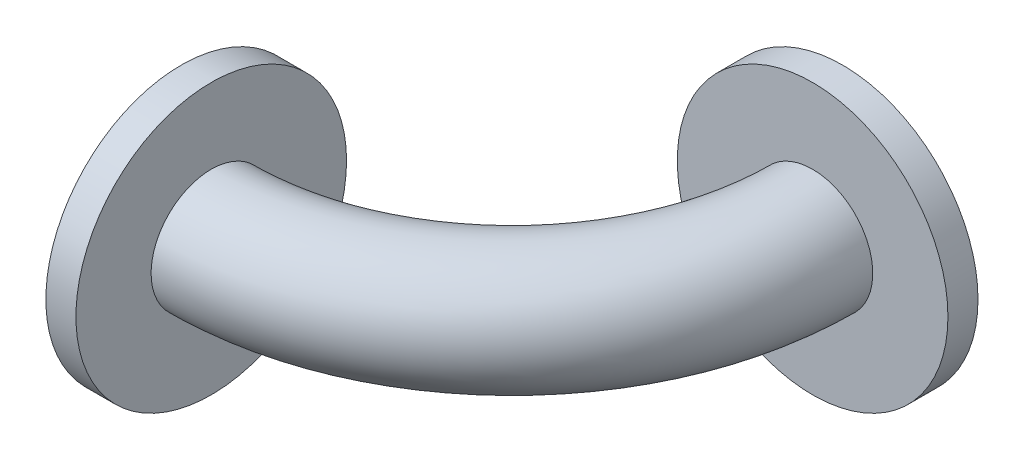
SolidWorks part; units mm, degrees
ref_plane "前视基准面" through (0, 0, 0) normal (0, 0, 1) x (1, 0, 0)
ref_plane "上视基准面" through (0, 0, 0) normal (0, 1, 0) x (1, 0, 0)
ref_plane "右视基准面" through (0, 0, 0) normal (1, 0, 0) x (0, 0, -1)
sketch "草图1" plane through (0, 0, 0) normal (0, 1, 0) x (1, 0, 0)
  arc A0 (40, 0) -> (0, -40) centre (0.0001, -0.0001) cw
sweep "扫描2" add path "草图1" circular profile diameter 16 parameters "D3"=16
ref_plane "基准面1" through (40, 0, 0) normal (1, 0, 0) x (0, 0, -1)
ref_plane "基准面2" through (0, 0, 40) normal (0, 0, 1) x (1, 0, 0)
sketch "草图9" plane through (0, 0, 0) normal (0, 0, 1) x (1, 0, 0)
  circle A0 centre (40, 0) radius 18
extrude "凸台-拉伸3" add sketch "草图9" against normal blind 4
sketch "草图10" plane through (0, 0, 0) normal (1, 0, 0) x (0, 0, -1)
  circle A0 centre (-40, 0) radius 18
extrude "凸台-拉伸4" add sketch "草图10" against normal blind 4
ref_plane "基准面3" through (0, 0, -4) normal (0, 0, 1) x (1, 0, 0)
ref_plane "基准面4" through (-4, 0, 0) normal (1, 0, 0) x (0, 0, -1)
